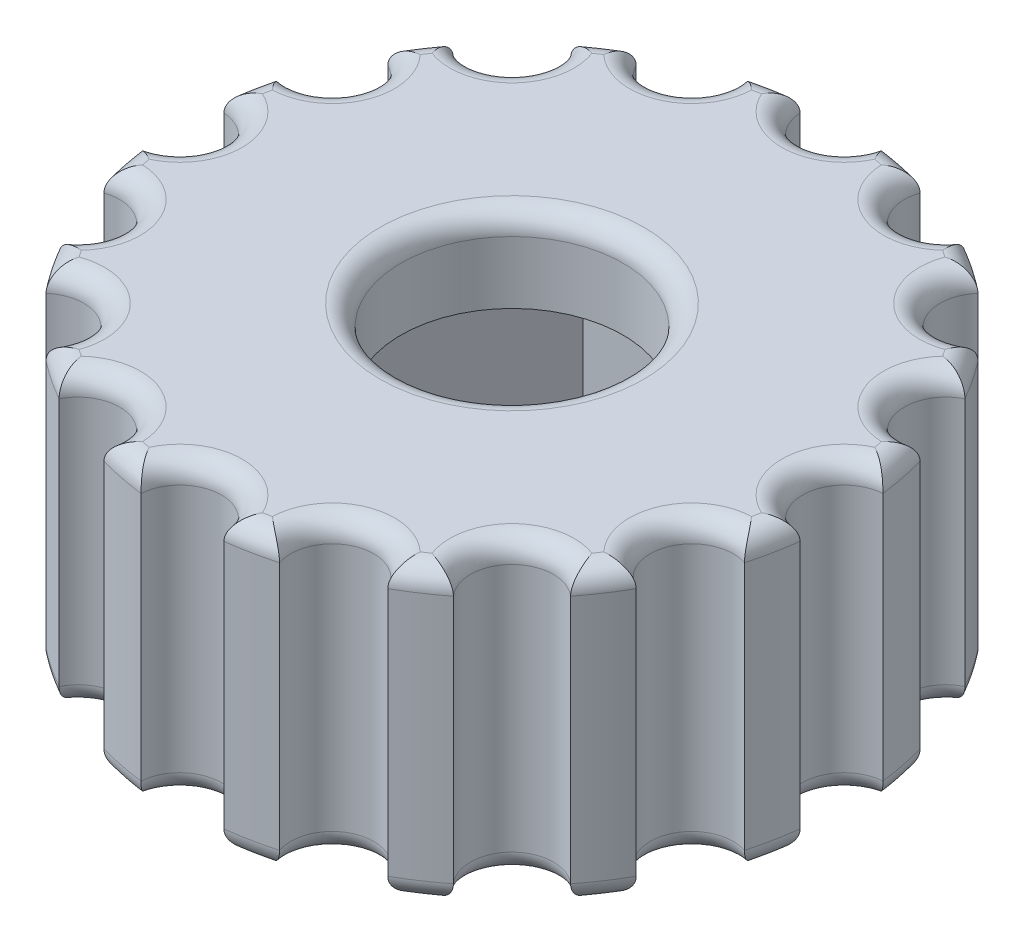
SolidWorks part; units mm, degrees
ref_plane "Front Plane" through (0, 0, 0) normal (0, 0, 1) x (1, 0, 0)
ref_plane "Top Plane" through (0, 0, 0) normal (0, 1, 0) x (1, 0, 0)
ref_plane "Right Plane" through (0, 0, 0) normal (1, 0, 0) x (0, 0, -1)
sketch "Sketch1" plane through (0, 0, 0) normal (0, 1, 0) x (1, 0, 0)
  line L0 (-2.3375, 4.0487) -> (-4.675, 0)
  line L1 (-4.675, 0) -> (-2.3375, -4.0487)
  line L2 (-2.3375, -4.0487) -> (2.3375, -4.0487)
  line L3 (2.3375, -4.0487) -> (4.675, 0)
  line L4 (4.675, 0) -> (2.3375, 4.0487)
  line L5 (2.3375, 4.0487) -> (-2.3375, 4.0487)
  circle A0 centre (0, 0) radius 8
  circle A1 centre (0, 0) radius 2.675
sketch "Sketch2" plane through (0, 0, 0) normal (0, 1, 0) x (1, 0, 0)
  line L0 (-2.3375, 4.0487) -> (-4.675, 0) construction
  line L1 (-4.675, 0) -> (-2.3375, -4.0487) construction
  line L2 (-2.3375, -4.0487) -> (2.3375, -4.0487) construction
  line L3 (2.3375, -4.0487) -> (4.675, 0) construction
  line L4 (4.675, 0) -> (2.3375, 4.0487) construction
  line L5 (2.3375, 4.0487) -> (-2.3375, 4.0487) construction
  line L6 (-2.3375, 4.0487) -> (-4.675, 0)
  line L7 (-4.675, 0) -> (-2.3375, -4.0487)
  line L8 (-2.3375, -4.0487) -> (2.3375, -4.0487)
  line L9 (2.3375, -4.0487) -> (4.675, 0)
  line L10 (4.675, 0) -> (2.3375, 4.0487)
  line L11 (2.3375, 4.0487) -> (-2.3375, 4.0487)
  circle A0 centre (0, 0) radius 8 construction
  circle A1 centre (0, 0) radius 8
extrude "Boss-Extrude1" add sketch "Sketch2" along normal mid plane 7
sketch "Sketch3" plane through (0, 3.5, 0) normal (0, 1, 0) x (1, 0, 0)
  circle A1 centre (0, 0) radius 8
  circle A2 centre (0, 0) radius 8
  dimension "D1" = 0
extrude "Boss-Extrude2" add sketch "Sketch3" against normal blind 2
sketch "Sketch4" plane through (0, 1.5, 0) normal (0, -1, 0) x (1, 0, 0)
  circle A0 centre (0, 0) radius 2.675 construction
  circle A1 centre (0, 0) radius 2.675
extrude "Cut-Extrude1" cut sketch "Sketch4" against normal through all both and the other way through all
sketch "Sketch5" plane through (0, -3.5, 0) normal (0, -1, 0) x (1, 0, 0)
  circle A0 centre (0, 8) radius 1
  circle A1 centre (0, 0) radius 8 construction
  circle A2 centre (3.0615, 7.391) radius 1
  circle A3 centre (5.6569, 5.6569) radius 1
  circle A4 centre (7.391, 3.0615) radius 1
  circle A5 centre (8, 0) radius 1
  circle A6 centre (7.391, -3.0615) radius 1
  circle A7 centre (5.6569, -5.6569) radius 1
  circle A8 centre (3.0615, -7.391) radius 1
  circle A9 centre (0, -8) radius 1
  circle A10 centre (-3.0615, -7.391) radius 1
  circle A11 centre (-5.6569, -5.6569) radius 1
  circle A12 centre (-7.391, -3.0615) radius 1
  circle A13 centre (-8, 0) radius 1
  circle A14 centre (-7.391, 3.0615) radius 1
  circle A15 centre (-5.6569, 5.6569) radius 1
  circle A16 centre (-3.0615, 7.391) radius 1
  point P37 (0, 0)
  dimension "D1" = 2
  dimension "D2" = 16
extrude "Cut-Extrude2" cut sketch "Sketch5" against normal through all both and the other way through all
fillet "Fillet1" radius 0.5 71 edges at (3.5062, -3.5, -2.0243) (3.5063, -3.5, 2.0243) (0, -3.5, 4.0487) (-3.5062, -3.5, 2.0243) (-3.5062, -3.5, -2.0243) (0, -3.5, -4.0487) (0, -3.5, 7) (1.5607, -3.5, 7.8463) (2.6788, -3.5, 6.4672) (4.4446, -3.5, 6.6518) (4.9497, -3.5, 4.9497) (6.6518, -3.5, 4.4446) (6.4672, -3.5, 2.6788) (7.8463, -3.5, 1.5607) (7, -3.5, 0) (7.8463, -3.5, -1.5607) (6.4672, -3.5, -2.6788) (6.6518, -3.5, -4.4446) (4.9497, -3.5, -4.9497) (4.4446, -3.5, -6.6518) (2.6788, -3.5, -6.4672) (1.5607, -3.5, -7.8463) (0, -3.5, -7) (-1.5607, -3.5, -7.8463) (-2.6788, -3.5, -6.4672) (-4.4446, -3.5, -6.6518) (-4.9497, -3.5, -4.9497) (-6.6518, -3.5, -4.4446) (-6.4672, -3.5, -2.6788) (-7.8463, -3.5, -1.5607) (-7, -3.5, 0) (-7.8463, -3.5, 1.5607) (-6.4672, -3.5, 2.6788) (-6.6518, -3.5, 4.4446) (-4.9497, -3.5, 4.9497) (-4.4446, -3.5, 6.6518) (-2.6788, -3.5, 6.4672) (-1.5607, -3.5, 7.8463) (0, 3.5, -2.675) (-4.4446, 3.5, 6.6518) (-4.9497, 3.5, 4.9497) (-6.6518, 3.5, 4.4446) (-6.4672, 3.5, 2.6788) (-7.8463, 3.5, 1.5607) (-7, 3.5, 0) (-7.8463, 3.5, -1.5607) (-6.4672, 3.5, -2.6788) (-6.6518, 3.5, -4.4446) (-4.9497, 3.5, -4.9497) (-4.4446, 3.5, -6.6518) (-2.6788, 3.5, -6.4672) (-1.5607, 3.5, -7.8463) (0, 3.5, -7) (1.5607, 3.5, -7.8463) (2.6788, 3.5, -6.4672) (4.4446, 3.5, -6.6518) (4.9497, 3.5, -4.9497) (6.6518, 3.5, -4.4446) (6.4672, 3.5, -2.6788) (7.8463, 3.5, -1.5607) (7, 3.5, 0) (7.8463, 3.5, 1.5607) (6.4672, 3.5, 2.6788) (6.6518, 3.5, 4.4446) (4.9497, 3.5, 4.9497) (4.4446, 3.5, 6.6518) (2.6788, 3.5, 6.4672) (1.5607, 3.5, 7.8463) (0, 3.5, 7) (-1.5607, 3.5, 7.8463) (-2.6788, 3.5, 6.4672)
sketch "Sketch6" plane through (0, 1.5, 0) normal (0, -1, 0) x (1, 0, 0)
  line L6 (-2.3375, -4.0487) -> (2.3375, -4.0487)
  line L7 (2.3375, -4.0487) -> (4.675, 0)
  line L8 (4.675, 0) -> (2.3375, 4.0487)
  line L9 (2.3375, 4.0487) -> (-2.3375, 4.0487)
  line L10 (-2.3375, 4.0487) -> (-4.675, 0)
  line L11 (-4.675, 0) -> (-2.3375, -4.0487)
  line L12 (-2.3375, -4.0487) -> (2.3375, -4.0487)
  line L13 (2.3375, -4.0487) -> (4.675, 0)
  line L14 (4.675, 0) -> (2.3375, 4.0487)
  line L15 (2.3375, 4.0487) -> (-2.3375, 4.0487)
  line L16 (-2.3375, 4.0487) -> (-4.675, 0)
  line L17 (-4.675, 0) -> (-2.3375, -4.0487)
  circle A0 centre (0, 0) radius 2.675 construction
  circle A1 centre (0, 0) radius 2.675
  dimension "D1" = 0
